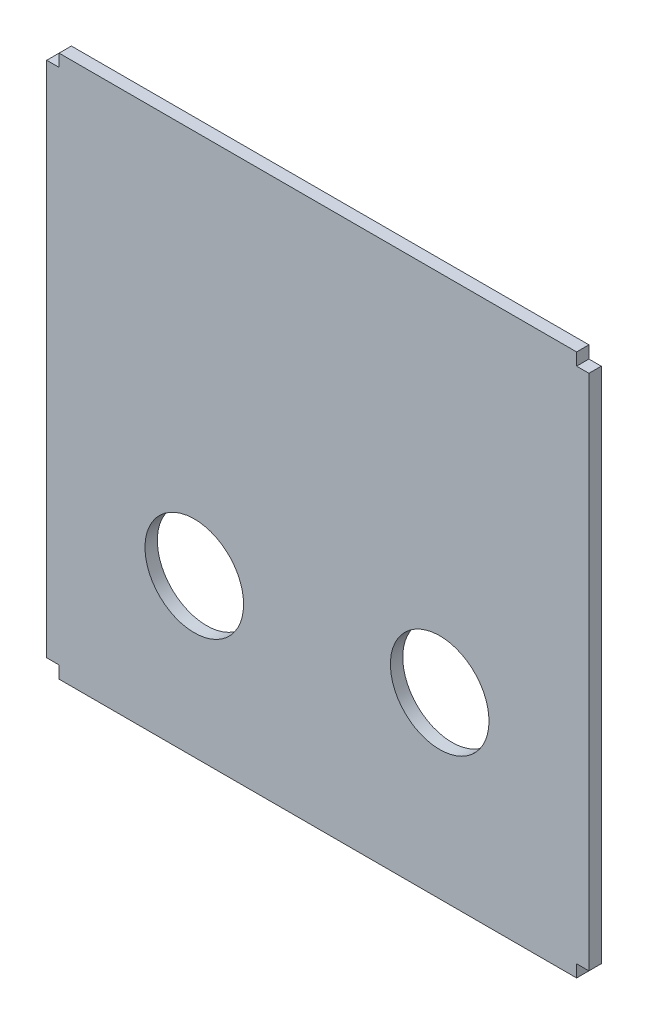
SolidWorks part; units mm, degrees
material "Acrylic (Medium-high impact)"
ref_plane "Front Plane" through (0, 0, 0) normal (0, 0, 1) x (1, 0, 0)
ref_plane "Top Plane" through (0, 0, 0) normal (0, 1, 0) x (1, 0, 0)
ref_plane "Right Plane" through (0, 0, 0) normal (1, 0, 0) x (0, 0, -1)
sketch "Sketch1" plane through (0, 0, 0) normal (0, 0, 1) x (1, 0, 0)
  line L1 (-139.7, -139.7) -> (139.7, -139.7)
  line L2 (-139.7, -139.7) -> (-139.7, 139.7)
  line L3 (-139.7, 139.7) -> (139.7, 139.7)
  line L4 (139.7, -139.7) -> (139.7, 139.7)
  line L5 (-139.7, -139.7) -> (139.7, 139.7) construction
  line L6 (-139.7, 139.7) -> (139.7, -139.7) construction
  point P0 (0, 0)
  dimension "D1" = 279.4
  dimension "D2" = 279.4
extrude "Boss-Extrude1" add sketch "Sketch1" along normal blind 6.35
sketch "Sketch3" plane through (0, 0, 6.35) normal (0, 0, 1) x (1, 0, 0)
  line L1 (0, 139.7) -> (0, -139.7) construction
  line L2 (139.7, 139.7) -> (-139.7, 139.7) construction
  line L3 (-139.7, -139.7) -> (139.7, -139.7) construction
  circle A3 centre (-63.669, -58.7375) radius 25.4
  circle A4 centre (62.7973, -47.625) radius 25.4
  circle A6 centre (-63.669, -58.7375) radius 25.4 construction
  arc A7 (81.2424, -65.0875) -> (44.3522, -65.0875) centre (62.7973, -47.625) ccw construction
extrude "Cut-Extrude2" cut sketch "Sketch3" against normal through all
sketch "Sketch4" plane through (0, 0, 6.35) normal (0, 0, 1) x (1, 0, 0)
  line L1 (-139.7, 139.7) -> (-133.35, 139.7)
  line L2 (-139.7, 139.7) -> (-139.7, 133.35)
  line L3 (-139.7, 133.35) -> (-133.35, 133.35)
  line L4 (-133.35, 139.7) -> (-133.35, 133.35)
  line L5 (139.7, 139.7) -> (133.35, 139.7)
  line L6 (139.7, 139.7) -> (139.7, 133.35)
  line L7 (139.7, 133.35) -> (133.35, 133.35)
  line L8 (133.35, 139.7) -> (133.35, 133.35)
  line L9 (139.7, -139.7) -> (133.35, -139.7)
  line L10 (139.7, -139.7) -> (139.7, -133.35)
  line L11 (139.7, -133.35) -> (133.35, -133.35)
  line L12 (133.35, -139.7) -> (133.35, -133.35)
  line L13 (-139.7, -139.7) -> (-133.35, -139.7)
  line L14 (-139.7, -139.7) -> (-139.7, -133.35)
  line L15 (-139.7, -133.35) -> (-133.35, -133.35)
  line L16 (-133.35, -139.7) -> (-133.35, -133.35)
  point P21 (-96.375, 96.375)
  dimension "D1" = 6.35
extrude "Cut-Extrude3" cut sketch "Sketch4" against normal through all
